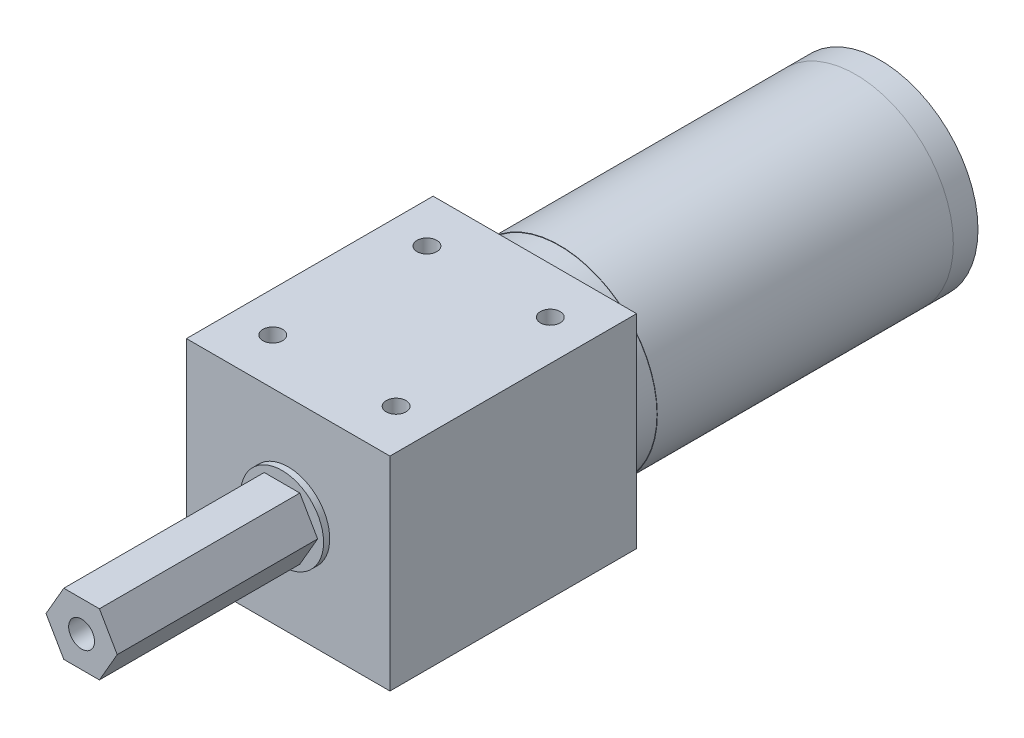
SolidWorks part; units mm, degrees
ref_plane "Front Plane" through (0, 0, 0) normal (0, 0, 1) x (1, 0, 0)
ref_plane "Top Plane" through (0, 0, 0) normal (0, 1, 0) x (1, 0, 0)
ref_plane "Right Plane" through (0, 0, 0) normal (1, 0, 0) x (0, 0, -1)
sketch "Sketch1" plane through (0, 0, 0) normal (0, 0, 1) x (1, 0, 0)
  line L1 (0, 0) -> (41.91, 0)
  line L2 (0, 0) -> (0, 41.91)
  line L3 (0, 41.91) -> (41.91, 41.91)
  line L4 (41.91, 0) -> (41.91, 41.91)
  line L5 (0, 0) -> (41.91, 41.91) construction
  line L6 (0, 41.91) -> (41.91, 0) construction
  point P4 (20.955, 20.955)
  dimension "D1" = 41.91
extrude "Boss-Extrude1" add sketch "Sketch1" along normal blind 50.8
sketch "Sketch2" plane through (0, 0, 50.8) normal (0, 0, 1) x (1, 0, 0)
  line L0 (20.955, 41.91) -> (20.955, 12.5165) construction
  line L1 (41.91, 41.91) -> (0, 41.91) construction
  line L2 (41.91, 20.955) -> (20.955, 20.955) construction
  line L3 (41.91, 0) -> (41.91, 41.91) construction
  line L5 (28.2873, 20.955) -> (24.6212, 27.305)
  line L6 (24.6212, 27.305) -> (17.2888, 27.305)
  line L7 (17.2888, 27.305) -> (13.6227, 20.955)
  line L8 (13.6227, 20.955) -> (17.2888, 14.605)
  line L9 (17.2888, 14.605) -> (24.6212, 14.605)
  line L10 (24.6212, 14.605) -> (28.2873, 20.955)
  circle A0 centre (20.955, 20.955) radius 6.35 construction
  dimension "D1" = 12.7
extrude "Boss-Extrude2" add sketch "Sketch2" along normal blind 42.545
sketch "Sketch3" plane through (0, 0, 0) normal (0, 0, -1) x (-1, 0, 0)
  line L0 (-20.955, 41.91) -> (-20.955, 13.8494) construction
  line L1 (-41.91, 41.91) -> (0, 41.91) construction
  line L2 (0, 20.955) -> (-20.955, 20.955) construction
  line L3 (0, 41.91) -> (0, 0) construction
  circle A0 centre (-20.955, 20.955) radius 20.066
  dimension "D1" = 40.132
extrude "Boss-Extrude3" add sketch "Sketch3" along normal blind 5.08
sketch "Sketch4" plane through (0, 0, -5.08) normal (0, 0, -1) x (-1, 0, 0)
  circle A0 centre (-20.955, 20.955) radius 20.1414
extrude "Boss-Extrude4" add sketch "Sketch4" along normal blind 60.96 separate body
sketch "Sketch5" plane through (0, 0, -66.04) normal (0, 0, -1) x (-1, 0, 0)
  circle A0 centre (-20.955, 20.955) radius 20.1414
extrude "Boss-Extrude5" add sketch "Sketch5" along normal blind 5.08 separate body
sketch "Sketch6" plane through (0, 0, 50.8) normal (0, 0, 1) x (1, 0, 0)
  line L0 (0, 0) -> (41.91, 41.91) construction
  circle A0 centre (20.955, 20.955) radius 8.5547
extrude "Boss-Extrude6" add sketch "Sketch6" along normal blind 1.27
sketch "Sketch7" plane through (0, 0, 93.345) normal (0, 0, 1) x (1, 0, 0)
  line L0 (17.2888, 27.305) -> (24.6212, 14.605) construction
  circle A0 centre (20.955, 20.955) radius 2.667
  dimension "D1" = 5.334
extrude "Cut-Extrude1" cut sketch "Sketch7" against normal blind 19.05
sketch "Sketch8" plane through (0, 41.91, 0) normal (0, 1, 0) x (1, 0, 0)
  line L0 (41.91, -25.4) -> (13.8615, -25.4) construction
  line L1 (8.255, -9.525) -> (33.655, -9.525) construction
  line L2 (8.255, -9.525) -> (8.255, -41.275) construction
  line L3 (8.255, -41.275) -> (33.655, -41.275) construction
  line L4 (33.655, -9.525) -> (33.655, -41.275) construction
  line L5 (8.255, -9.525) -> (33.655, -41.275) construction
  line L6 (8.255, -41.275) -> (33.655, -9.525) construction
  line L7 (41.91, -50.8) -> (41.91, 0) construction
  line L8 (20.955, -50.8) -> (20.955, -25.4) construction
  line L9 (41.91, -50.8) -> (0, -50.8) construction
  circle A0 centre (33.655, -9.525) radius 2.032
  circle A1 centre (8.255, -9.525) radius 2.032
  circle A2 centre (8.255, -41.275) radius 2.032
  circle A3 centre (33.655, -41.275) radius 2.032
  point P0 (20.955, -25.4)
  dimension "D3" = 4.064
  dimension "D1" = 31.75
  dimension "D2" = 25.4
extrude "Cut-Extrude2" cut sketch "Sketch8" against normal blind 8.89
ref_plane "Plane1" through (0, 20.955, 0) normal (0, 1, 0) x (1, 0, 0)
mirror "Mirror1" about plane through (0, 20.955, 0) normal (0, 1, 0) of "Cut-Extrude2"
